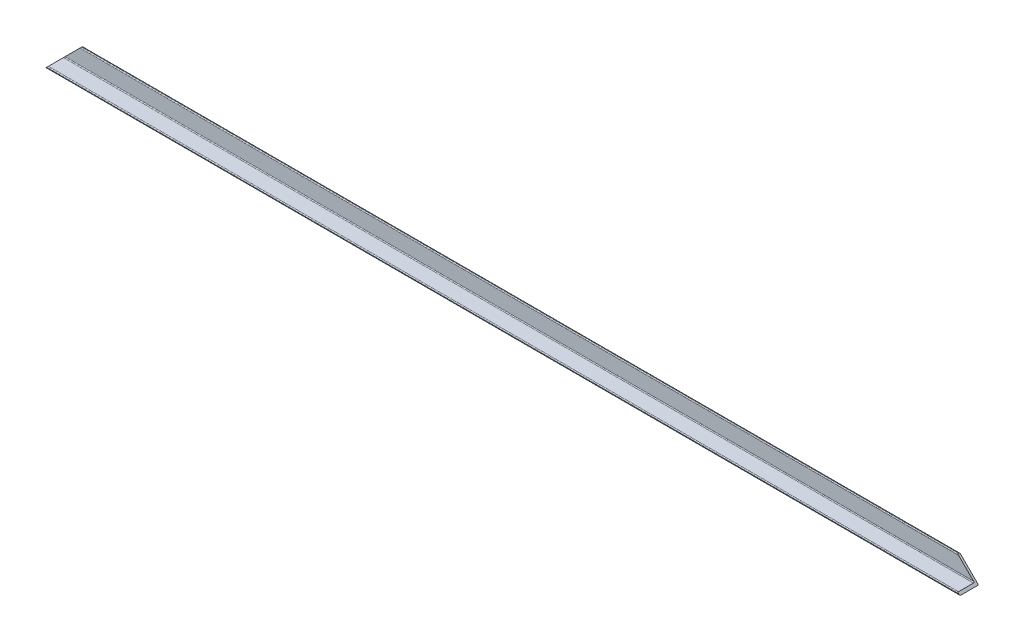
SolidWorks part; units mm, degrees
ref_plane "Front Plane" through (0, 0, 0) normal (0, 0, 1) x (1, 0, 0)
ref_plane "Top Plane" through (0, 0, 0) normal (0, 1, 0) x (1, 0, 0)
ref_plane "Right Plane" through (0, 0, 0) normal (1, 0, 0) x (0, 0, -1)
sketch "Sketch1" plane through (0, 0, 0) normal (0, 1, 0) x (1, 0, 0)
  line L1 (-557.5, 11.25) -> (557.5, 11.25)
  line L2 (-557.5, 11.25) -> (-557.5, -11.25)
  line L3 (-557.5, -11.25) -> (557.5, -11.25)
  line L4 (557.5, 11.25) -> (557.5, -11.25)
  line L5 (-557.5, 11.25) -> (557.5, -11.25) construction
  line L6 (-557.5, -11.25) -> (557.5, 11.25) construction
  point P0 (0, 0)
  dimension "D1" = 1115
  dimension "D2" = 22.5
extrude "Boss-Extrude1" add sketch "Sketch1" along normal blind 2.5
sketch "Sketch2" plane through (0, 2.5, 0) normal (0, 1, 0) x (1, 0, 0)
  line L0 (557.5, -11.25) -> (557.5, 11.25) construction
  line L1 (-557.5, 11.25) -> (557.5, 11.25)
  line L2 (-557.5, 11.25) -> (-557.5, 8.75)
  line L3 (-557.5, 8.75) -> (557.5, 8.75)
  line L4 (557.5, 11.25) -> (557.5, 8.75)
  dimension "D1" = 2.5
extrude "Boss-Extrude2" add sketch "Sketch2" along normal blind 20
sketch "Sketch3" plane through (0, 0, -8.75) normal (0, 0, 1) x (1, 0, 0)
  line L0 (-557.5, 22.5) -> (-557.5, -7.5)
  line L1 (-557.5, 22.5) -> (557.5, 22.5) construction
  line L2 (-557.5, -7.5) -> (-527.5, 22.5)
  line L3 (-527.5, 22.5) -> (-557.5, 22.5)
  line L4 (557.5, 22.5) -> (557.5, -7.5)
  line L5 (557.5, -7.5) -> (527.5, 22.5)
  line L6 (527.5, 22.5) -> (557.5, 22.5)
  dimension "D1" = 30
  dimension "D2" = 30
  dimension "D3" = 45
  dimension "D4" = 45
extrude "Cut-Extrude1" cut sketch "Sketch3" against normal blind 25 and the other way through all
fillet "Fillet2" radius 1 6 edges at (0, 0, -11.25) (0, 0, 11.25) (0, 2.5, 11.25) (0, 22.5, -11.25) (0, 22.5, -8.75) (0, 2.5, -8.75)
